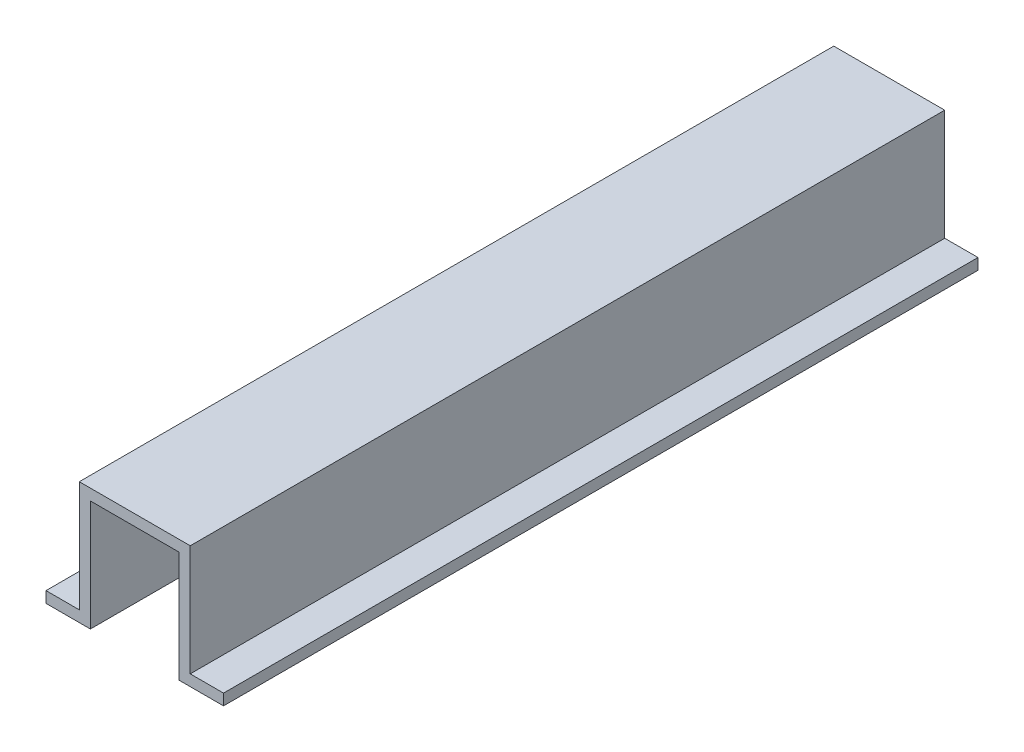
SolidWorks part; units mm, degrees
ref_plane "Front Plane" through (0, 0, 0) normal (0, 0, 1) x (1, 0, 0)
ref_plane "Top Plane" through (0, 0, 0) normal (0, 1, 0) x (1, 0, 0)
ref_plane "Right Plane" through (0, 0, 0) normal (1, 0, 0) x (0, 0, -1)
sketch "10 mm deep hat section profile" plane through (0, 0, 0) normal (0, 0, 1) x (1, 0, 0)
  line L0 (-8, 7) -> (-4, 7)
  line L1 (-4, 7) -> (-4, 17)
  line L2 (-4, 17) -> (4, 17)
  line L3 (4, 17) -> (4, 7)
  line L4 (4, 7) -> (8, 7)
  line L5 (8, 7) -> (8, 8)
  line L6 (8, 8) -> (5, 8)
  line L7 (5, 8) -> (5, 18)
  line L8 (5, 18) -> (-5, 18)
  line L9 (-5, 18) -> (-5, 8)
  line L10 (-5, 8) -> (-8, 8)
  line L11 (-8, 8) -> (-8, 7)
extrude "10 mm deep hat section" add sketch "10 mm deep hat section profile" along normal blind 68
